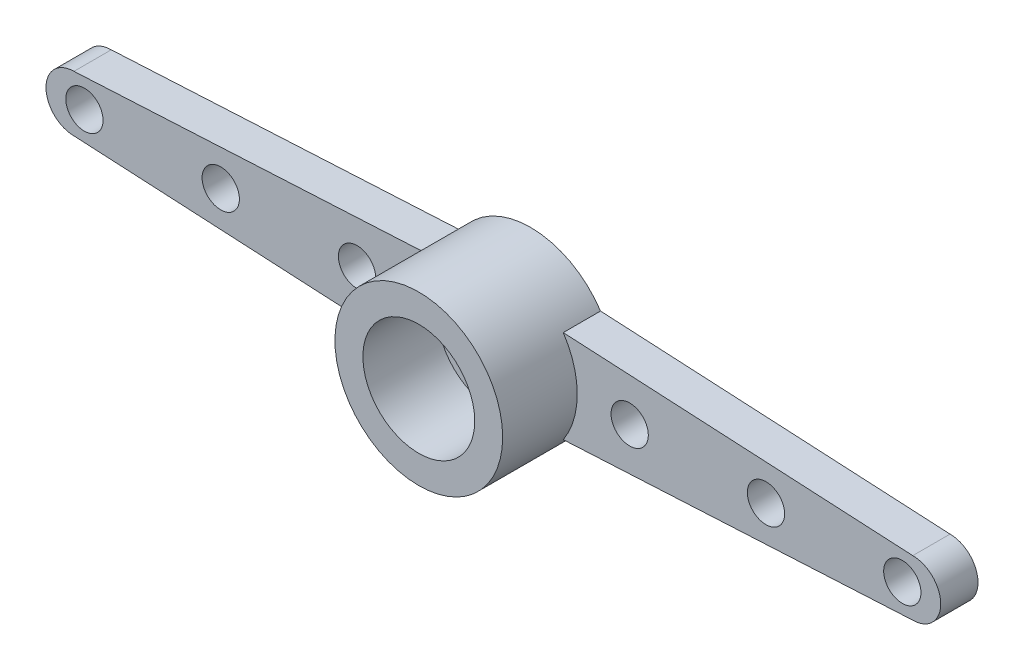
SolidWorks part; units mm, degrees
material "Polybutadiene (PB)"
ref_plane "Front Plane" through (0, 0, 0) normal (0, 0, 1) x (1, 0, 0)
ref_plane "Top Plane" through (0, 0, 0) normal (0, 1, 0) x (1, 0, 0)
ref_plane "Right Plane" through (0, 0, 0) normal (1, 0, 0) x (0, 0, -1)
sketch "Sketch1" plane through (0, 0, 0) normal (0, 0, 1) x (1, 0, 0)
  line L0 (-22.5, 0) -> (22.5, 0) construction
  line L1 (24, -6.5) -> (-24, -6.5)
  line L2 (24, -6.5) -> (24, 6.5)
  line L3 (24, 6.5) -> (-24, 6.5)
  line L4 (-24, -6.5) -> (-24, 6.5)
  line L5 (24, -6.5) -> (-24, 6.5) construction
  line L6 (24, 6.5) -> (-24, -6.5) construction
  line L7 (-22.5, 1.5) -> (-3.75, 2.4875)
  line L8 (22.5, 1.5) -> (3.75, 2.4875)
  line L9 (22.5, -1.5) -> (3.75, -2.4875)
  line L10 (-22.5, -1.5) -> (-3.75, -2.4875)
  circle A0 centre (0, 0) radius 4.5
  circle A1 centre (-22.5, 0) radius 1.5
  circle A2 centre (22.5, 0) radius 1.5
  point P0 (0, 0)
  dimension "D3" = 9
  dimension "D4" = 3
  dimension "D1" = 13
  dimension "D2" = 48
  dimension "D5" = 7.5
extrude "Boss-Extrude1" add sketch "Sketch1" along normal blind 6
sketch "Sketch3" plane through (0, 0, 6) normal (0, 0, 1) x (1, 0, 0)
  line L4 (-22.5, -1.5) -> (-3.75, -2.4875)
  line L5 (3.75, -2.4875) -> (22.5, -1.5)
  line L6 (22.5, 1.5) -> (3.75, 2.4875)
  line L7 (-3.75, 2.4875) -> (-22.5, 1.5)
  line L8 (-22.5, -1.5) -> (-3.75, -2.4875)
  line L9 (3.75, -2.4875) -> (22.5, -1.5)
  line L10 (22.5, 1.5) -> (3.75, 2.4875)
  line L11 (-3.75, 2.4875) -> (-22.5, 1.5)
  circle A0 centre (0, 0) radius 4.5
  circle A1 centre (0, 0) radius 3
  arc A4 (-22.5, 1.5) -> (-22.5, -1.5) centre (-22.5, 0) ccw
  arc A5 (-3.75, -2.4875) -> (3.75, -2.4875) centre (0, 0) ccw
  arc A6 (22.5, -1.5) -> (22.5, 1.5) centre (22.5, 0) ccw
  arc A7 (3.75, 2.4875) -> (-3.75, 2.4875) centre (0, 0) ccw
  arc A8 (-22.5, 1.5) -> (-22.5, -1.5) centre (-22.5, 0) ccw
  arc A9 (-3.75, -2.4875) -> (3.75, -2.4875) centre (0, 0) ccw
  arc A10 (22.5, -1.5) -> (22.5, 1.5) centre (22.5, 0) ccw
  arc A11 (3.75, 2.4875) -> (-3.75, 2.4875) centre (0, 0) ccw
  arc M9 (-22.5, 1.5) -> (-22.5, -1.5) centre (-22.5, 0) ccw
  line M10 (-22.5, -1.5) -> (-3.75, -2.4875)
  line M12 (3.75, -2.4875) -> (22.5, -1.5)
  arc M13 (22.5, -1.5) -> (22.5, 1.5) centre (22.5, 0) ccw
  line M14 (22.5, 1.5) -> (3.75, 2.4875)
  line M16 (-3.75, 2.4875) -> (-22.5, 1.5)
  dimension "D2" = 6
  dimension "D1" = 0
extrude "Cut-Extrude1" cut sketch "Sketch3" against normal blind 4 contours A0 M16 M9 M10 | A0 M12 M13 M14 | A1
sketch "Sketch4" plane through (0, 0, 0) normal (0, 0, -1) x (-1, 0, 0)
  circle A0 centre (0, 0) radius 1
  circle A1 centre (7.3129, 0) radius 1
  circle A2 centre (14.6258, 0) radius 1
  circle A3 centre (21.9387, 0) radius 1
  point P2 (6.6747, 0)
  point P4 (7.3129, 0)
  dimension "D1" = 2
  dimension "D2" = 4
extrude "Cut-Extrude2" cut sketch "Sketch4" against normal blind 10
mirror "Mirror1" about plane through (0, 0, 0) normal (1, 0, 0) of "Cut-Extrude2"
